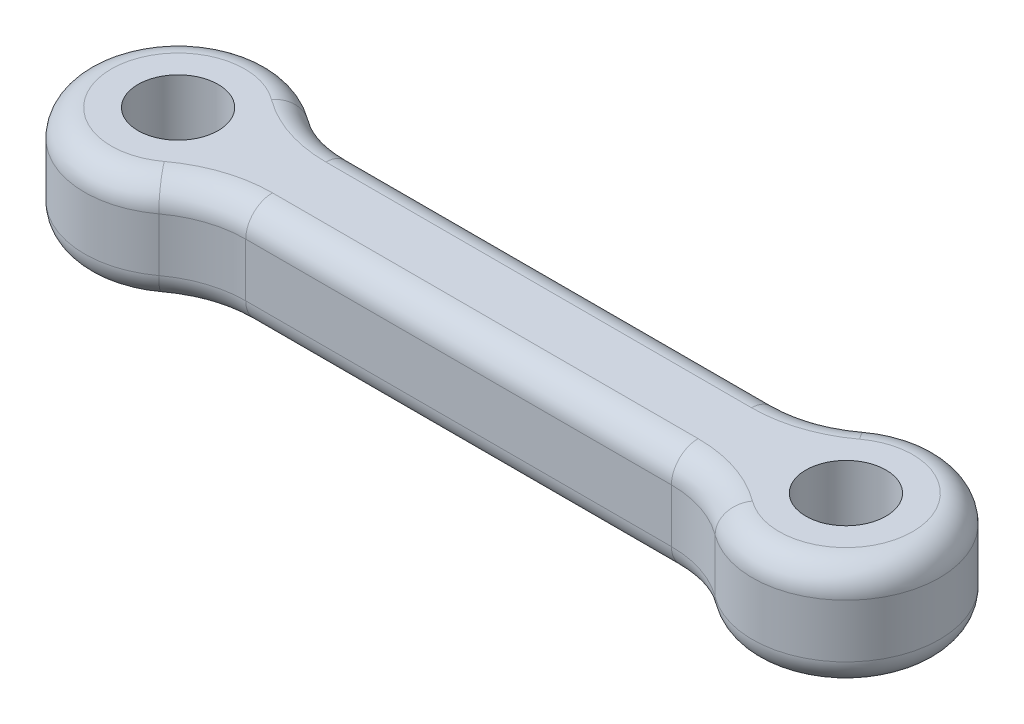
SolidWorks part; units mm, degrees
ref_plane "Front Plane" through (0, 0, 0) normal (0, 0, 1) x (1, 0, 0)
ref_plane "Top Plane" through (0, 0, 0) normal (0, 1, 0) x (1, 0, 0)
ref_plane "Right Plane" through (0, 0, 0) normal (1, 0, 0) x (0, 0, -1)
sketch "Sketch2" plane through (0, 0, 0) normal (0, 1, 0) x (1, 0, 0)
  line L0 (12.5, 14.9104) -> (12.5, -11.6235) construction
  line L1 (0, 0) -> (12.5, 0) construction
  line L2 (4.5328, -2) -> (20.4672, -2)
  line L3 (4.5328, 2) -> (20.4672, 2)
  line L4 (0, 0) -> (-4.96, 0) construction
  line L5 (0, 2) -> (12.5, 2) construction
  line L6 (25, 0) -> (29.96, 0) construction
  line L7 (25, 0) -> (12.5, 0) construction
  arc A0 (2.0878, 2.8091) -> (2.0878, -2.8091) centre (0, 0) ccw
  circle A2 centre (0, 0) radius 1.5
  arc A3 (2.0878, 2.8091) -> (4.5328, 2) centre (4.5328, 6.0989) ccw
  arc A4 (2.0878, -2.8091) -> (4.5328, -2) centre (4.5328, -6.0989) cw
  arc A5 (22.9122, -2.8091) -> (20.4672, -2) centre (20.4672, -6.0989) ccw
  arc A6 (22.9122, 2.8091) -> (20.4672, 2) centre (20.4672, 6.0989) cw
  circle A7 centre (25, 0) radius 1.5
  arc A8 (22.9122, 2.8091) -> (22.9122, -2.8091) centre (25, 0) cw
  point P25 (12.5, -2)
  dimension "D2" = 3
  dimension "D3" = 7
  dimension "D1" = 12.5
  dimension "D5" = 2
extrude "Boss-Extrude1" add sketch "Sketch2" along normal blind 4
fillet "Fillet1" radius 1 16 edges at (3.2451, 4, 2.2075) (-3.5, 4, 0) (3.2451, 4, -2.2075) (12.5, 4, -2) (21.7549, 4, -2.2075) (28.5, 4, 0) (21.7549, 4, 2.2075) (3.2451, 0, 2.2075) (-3.5, 0, 0) (3.2451, 0, -2.2075) (12.5, 0, -2) (21.7549, 0, -2.2075) (28.5, 0, 0) (21.7549, 0, 2.2075) (12.5, 4, 2) (12.5, 0, 2)
